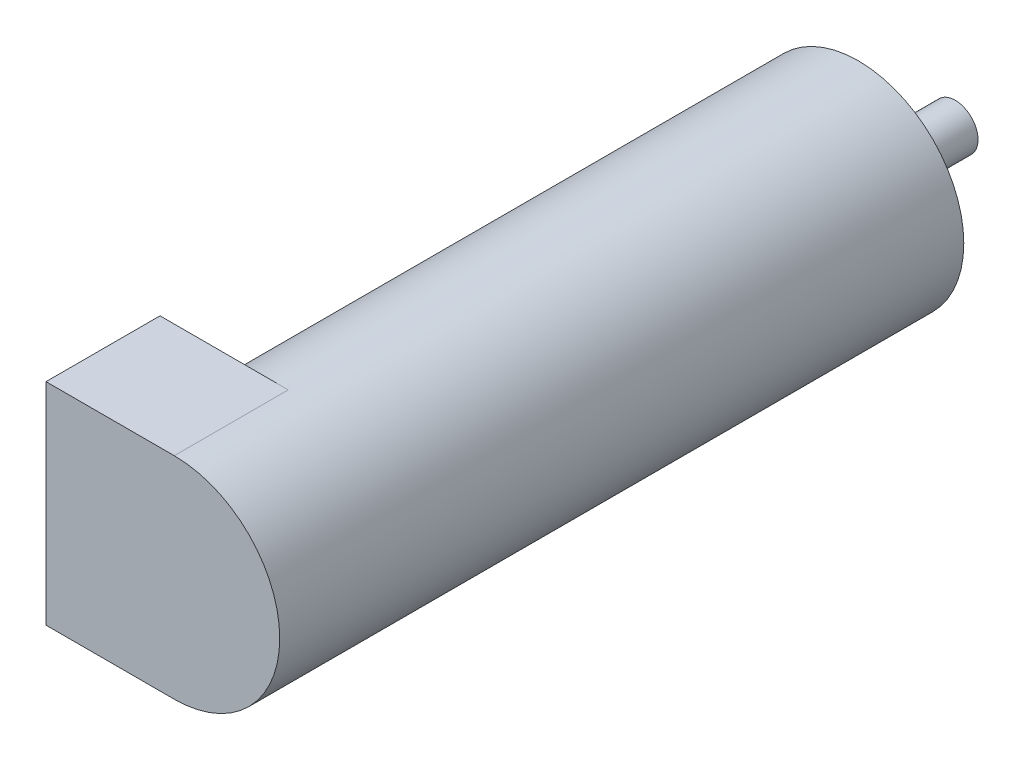
SolidWorks part; units mm, degrees
ref_plane "Спереди" through (0, 0, 0) normal (0, 0, 1) x (1, 0, 0)
ref_plane "Сверху" through (0, 0, 0) normal (0, 1, 0) x (1, 0, 0)
ref_plane "Справа" through (0, 0, 0) normal (1, 0, 0) x (0, 0, -1)
sketch "Эскиз1" plane through (0, 0, 0) normal (0, 0, 1) x (1, 0, 0)
  circle A0 centre (0, 0) radius 18.5
  dimension "D1" = 37
extrude "Бобышка-Вытянуть1" add sketch "Эскиз1" along normal blind 100
sketch "Эскиз2" plane through (0, 0, 100) normal (0, 0, 1) x (1, 0, 0)
  line L0 (0, 18.5) -> (-22.5, 18.5)
  line L1 (-22.5, 18.5) -> (-22.5, -18.5)
  line L2 (-22.5, -18.5) -> (0, -18.5)
  line L3 (18.5, 0) -> (18.5, 36.1764) construction
  circle A0 centre (0, 0) radius 18.5 construction
  arc A1 (0, -18.5) -> (0, 18.5) centre (0, 0) ccw
  dimension "D1" = 41
extrude "Бобышка-Вытянуть2" add sketch "Эскиз2" along normal blind 20
sketch "Эскиз3" plane through (0, 0, 0) normal (0, 0, -1) x (-1, 0, 0)
  circle A0 centre (0, 0) radius 4
  dimension "D1" = 8
extrude "Бобышка-Вытянуть3" add sketch "Эскиз3" along normal blind 17
sketch "Эскиз4" plane through (0, 0, 0) normal (0, 0, -1) x (-1, 0, 0)
  line L0 (0, 0) -> (0, -18.1277) construction
  line L1 (6.3408, 0) -> (24.5695, 0) construction
  circle A0 centre (15, 0) radius 1.5
  circle A1 centre (0, 15) radius 1.5
  circle A2 centre (-15, 0) radius 1.5
  circle A3 centre (0, -15) radius 1.5
  dimension "D1" = 3
  dimension "D2" = 15
  dimension "D3" = 15
extrude "Вырез-Вытянуть1" cut sketch "Эскиз4" against normal blind 3
